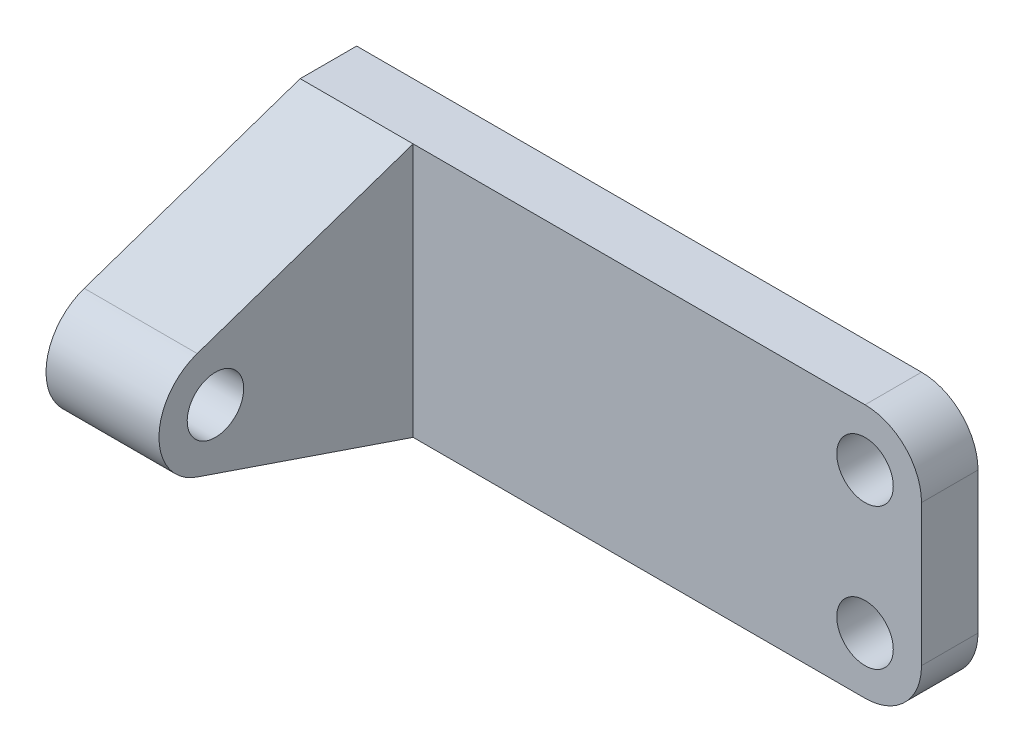
SolidWorks part; units mm, degrees
ref_plane "Front Plane" through (0, 0, 0) normal (0, 0, 1) x (1, 0, 0)
ref_plane "Top Plane" through (0, 0, 0) normal (0, 1, 0) x (1, 0, 0)
ref_plane "Right Plane" through (0, 0, 0) normal (1, 0, 0) x (0, 0, -1)
sketch "Sketch1" plane through (0, 0, 0) normal (0, 0, 1) x (1, 0, 0)
  line L0 (72.8067, 70.7391) -> (-54.1933, 70.7391)
  line L1 (-54.1933, 70.7391) -> (-54.1933, 13.5891)
  line L2 (-54.1933, 13.5891) -> (72.8067, 13.5891)
  line L3 (85.5067, 58.0391) -> (85.5067, 26.2891)
  arc A0 (85.5067, 58.0391) -> (72.8067, 70.7391) centre (72.8067, 58.0391) ccw
  arc A1 (72.8067, 13.5891) -> (85.5067, 26.2891) centre (72.8067, 26.2891) ccw
  circle A2 centre (72.8067, 58.0391) radius 6.35
  circle A3 centre (72.8067, 26.2891) radius 6.35
  dimension "D1" = 12.7
  dimension "D2" = 12.7
  dimension "D5" = 12.7
  dimension "D6" = 12.7
  dimension "D7" = 12.7
  dimension "D3" = 127
  dimension "D4" = 57.15
extrude "Boss-Extrude2" add sketch "Sketch1" along normal blind 12.7
sketch "Sketch2" plane through (-54.1933, 0, 0) normal (-1, 0, 0) x (0, 0, 1)
  line L0 (12.7, 70.7391) -> (61.2488, 54.1845)
  line L1 (12.7, 13.5891) -> (61.2488, 30.1437)
  line L2 (0, 70.7391) -> (0, 13.5891) construction
  arc A0 (61.2488, 30.1437) -> (61.2488, 54.1845) centre (57.15, 42.1641) ccw
  circle A1 centre (57.15, 42.1641) radius 6.35
  line M3 (12.7, 13.5891) -> (12.7, 70.7391)
  dimension "D1" = 12.7
  dimension "D2" = 69.85
  dimension "D3" = 12.7
extrude "Boss-Extrude3" add sketch "Sketch2" against normal blind 25.4 contours L1 A0 L0 A1 M3
